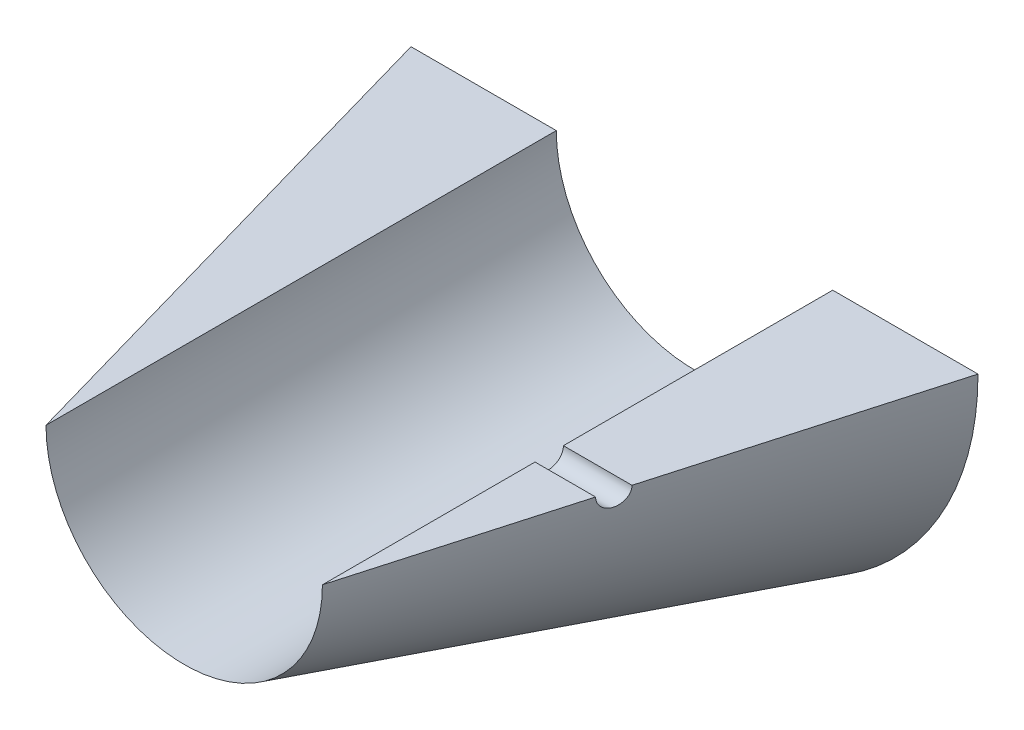
SolidWorks part; units mm, degrees
ref_plane "Plan de face" through (0, 0, 0) normal (0, 0, 1) x (1, 0, 0)
ref_plane "Plan de dessus" through (0, 0, 0) normal (0, 1, 0) x (1, 0, 0)
ref_plane "Plan de droite" through (0, 0, 0) normal (1, 0, 0) x (0, 0, -1)
sketch "Esquisse1" plane through (0, 0, 0) normal (0, 0, 1) x (1, 0, 0)
  circle A0 centre (0, 0) radius 100
  circle A1 centre (0, 0) radius 48.75
  dimension "D1" = 200
  dimension "D2" = 97.5
ref_plane "Plan1" through (0, 0, 180) normal (0, 0, 1) x (1, 0, 0)
sketch "Esquisse2" plane through (0, 0, 180) normal (0, 0, 1) x (1, 0, 0)
  circle A0 centre (0, 0) radius 48.75
  dimension "D1" = 97.5
sketch "Esquisse4" plane through (0, 0, 0) normal (1, 0, 0) x (0, 0, -1)
  line L0 (-180, 48.75) -> (0, 100)
  line L6 (-180, 48.75) -> (0, 48.75)
  line L9 (0, 48.75) -> (0, 100)
ref_axis "Axe1" through (0, 0, 180) along (0, 0, -1)
revolve "Révolution1" add sketch "Esquisse4" angle 360 about axis through (0, 0, 180) along (0, 0, -1)
ref_plane "Plan2" through (0, 0, 100) normal (0, 0, 1) x (1, 0, 0)
sketch "Esquisse6" plane through (0, 0, 100) normal (0, 0, 1) x (1, 0, 0)
  line L0 (0, 0) -> (274.7687, 64.6899)
sketch "Esquisse7" plane through (0, 0, 0) normal (1, 0, 0) x (0, 0, -1)
  circle A0 centre (-100, 0) radius 5
  dimension "D1" = 10
extrude "Enlèv. mat.-Extru.1" cut sketch "Esquisse7" along normal up to surface (72.9514 mm away) contours A0
other "Enlèv. mat.-Surface1"
